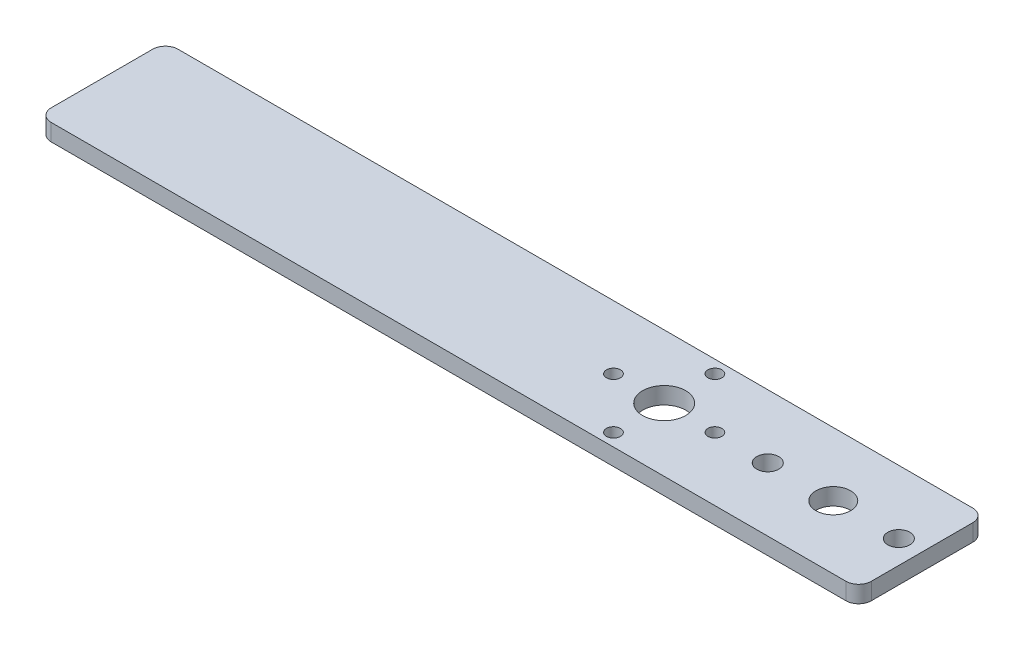
SolidWorks part; units mm, degrees
ref_plane "前视基准面" through (0, 0, 0) normal (0, 0, 1) x (1, 0, 0)
ref_plane "上视基准面" through (0, 0, 0) normal (0, 1, 0) x (1, 0, 0)
ref_plane "右视基准面" through (0, 0, 0) normal (1, 0, 0) x (0, 0, -1)
sketch "草图2" plane through (0, 0, 0) normal (0, 1, 0) x (1, 0, 0)
  line L1 (-42, 15) -> (146, 15)
  line L2 (-45, 12) -> (-45, -12)
  line L3 (-42, -15) -> (146, -15)
  line L4 (149, 12) -> (149, -12)
  circle A1 centre (88, 0) radius 5.1
  circle A2 centre (128, 0) radius 4.1
  circle A3 centre (88, 12) radius 1.65
  circle A4 centre (88, -12) radius 1.65
  circle A5 centre (76, 0) radius 1.65
  circle A7 centre (100, 0) radius 1.65
  arc A10 (149, -12) -> (146, -15) centre (146, -12) cw
  arc A11 (149, 12) -> (146, 15) centre (146, 12) ccw
  arc A12 (-45, 12) -> (-42, 15) centre (-42, 12) cw
  arc A13 (-42, -15) -> (-45, -12) centre (-42, -12) cw
  circle A14 centre (143.5, 0) radius 2.6
  circle A15 centre (112.5, 0) radius 2.6
  point P0 (0, 0)
  point P9 (149, -15)
  point P32 (-45, -15)
  dimension "D3" = 5.2
  dimension "D4" = 3.3
  dimension "D7" = 88
  dimension "D5" = 3
  dimension "D2" = 8.2
  dimension "D6" = 76
  dimension "D8" = 100
  dimension "D9" = 112.5
  dimension "D10" = 128
  dimension "D11" = 143.5
  dimension "D12" = 149
  dimension "D13" = 45
  dimension "D15" = 15
  dimension "D1" = 10.2
  dimension "D14" = 15
extrude "凸台-拉伸2" add sketch "草图2" along normal blind 4
